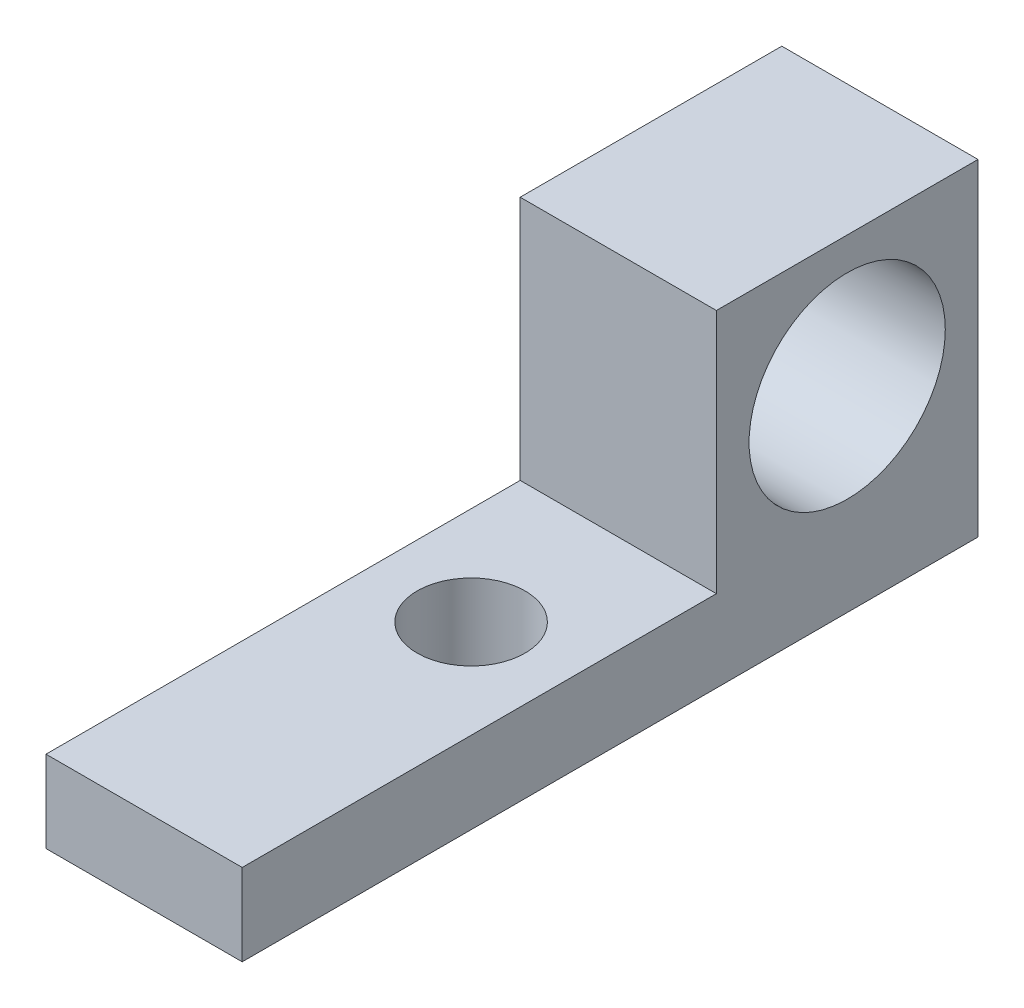
SolidWorks part; units mm, degrees
material "6061-T6 (SS)"
ref_plane "Front Plane" through (0, 0, 0) normal (0, 0, 1) x (1, 0, 0)
ref_plane "Top Plane" through (0, 0, 0) normal (0, 1, 0) x (1, 0, 0)
ref_plane "Right Plane" through (0, 0, 0) normal (1, 0, 0) x (0, 0, -1)
sketch "Sketch1" plane through (0, 0, 0) normal (1, 0, 0) x (0, 0, -1)
  line L0 (0, 0) -> (45, 0)
  line L1 (45, 0) -> (45, 20)
  line L2 (45, 20) -> (29, 20)
  line L3 (29, 20) -> (29, 5)
  line L4 (29, 5) -> (0, 5)
  line L5 (0, 5) -> (0, 0)
  line L6 (37, 20) -> (37, 0) construction
  circle A0 centre (37, 12) radius 6
  dimension "D4" = 12
  dimension "D1" = 20
  dimension "D2" = 16
  dimension "D3" = 45
  dimension "D5" = 12
  dimension "D6" = 5
extrude "Boss-Extrude1" add sketch "Sketch1" along normal blind 12
hole_wizard "M6 Clearance Hole1" positions "Sketch3" profile "Sketch2" hole size "M6" standard "ISO" end condition up to next
sketch "Sketch3" plane through (0, 5, 0) normal (0, 1, 0) x (-1, 0, 0)
  line L0 (-6, 0) -> (-6, -29) construction
  line L1 (-12, 0) -> (0, 0) construction
  line L2 (-12, -29) -> (0, -29) construction
  point P0 (-6, -20)
  dimension "D2" = 20
sketch "Sketch2" plane through (6, 5, -20) normal (1, 0, 0) x (0, 0, 1)
  line L0 (0, 0) -> (0, 5)
  line L1 (0, 5) -> (3.3, 5)
  line L2 (3.3, 5) -> (3.3, 0)
  line L5 (3.3, 0) -> (0, 0)
  line L11 (0, -6.35) -> (0, 107.95) construction
  dimension "Thru Hole Dia." = 6.6
  dimension "Thru Hole Depth" = 5
